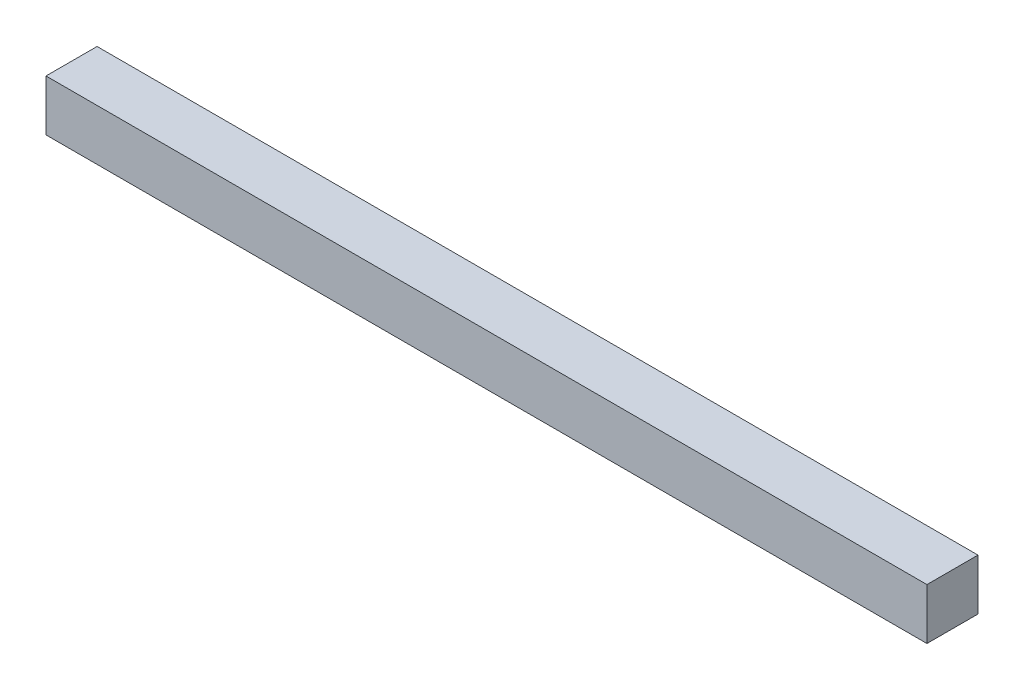
SolidWorks part; units mm, degrees
ref_plane "Front Plane" through (0, 0, 0) normal (0, 0, 1) x (1, 0, 0)
ref_plane "Top Plane" through (0, 0, 0) normal (0, 1, 0) x (1, 0, 0)
ref_plane "Right Plane" through (0, 0, 0) normal (1, 0, 0) x (0, 0, -1)
sketch "Sketch1" plane through (0, 0, 0) normal (1, 0, 0) x (0, 0, -1)
  line L1 (-20, 20) -> (20, 20)
  line L2 (-20, 20) -> (-20, -20)
  line L3 (-20, -20) -> (20, -20)
  line L4 (20, 20) -> (20, -20)
  dimension "D1" = 40
  dimension "D2" = 40
extrude "Boss-Extrude1" add sketch "Sketch1" along normal blind 690
